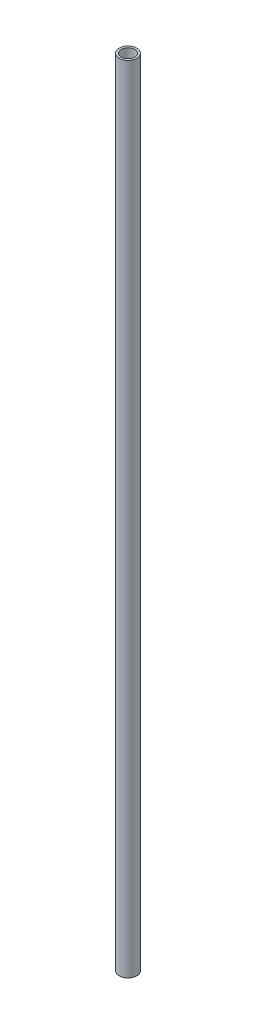
SolidWorks part; units mm, degrees
material "PVC 0.007 Plastificado"
ref_plane "Alzado" through (0, 0, 0) normal (0, 0, 1) x (1, 0, 0)
ref_plane "Planta" through (0, 0, 0) normal (0, 1, 0) x (1, 0, 0)
ref_plane "Vista lateral" through (0, 0, 0) normal (1, 0, 0) x (0, 0, -1)
sketch "Croquis1" plane through (0, 0, 0) normal (0, 1, 0) x (1, 0, 0)
  circle A0 centre (0, 0) radius 16.7
  dimension "D1" = 33.4
extrude "Saliente-Extruir1" add sketch "Croquis1" along normal blind 1500
sketch "Croquis2" plane through (0, 1500, 0) normal (0, 1, 0) x (1, 0, 0)
  circle A0 centre (0, 0) radius 12.7
  dimension "D1" = 25.4
extrude "Cortar-Extruir1" cut sketch "Croquis2" against normal through all
